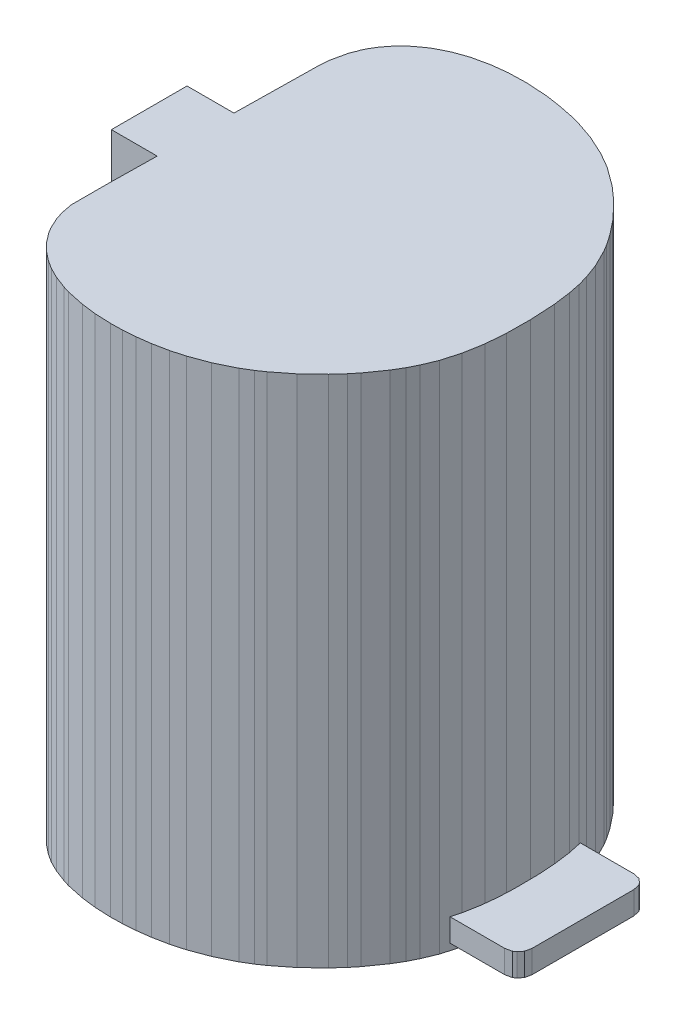
SolidWorks part; units mm, degrees
ref_plane "Front Plane" through (0, 0, 0) normal (0, 0, 1) x (1, 0, 0)
ref_plane "Top Plane" through (0, 0, 0) normal (0, 1, 0) x (1, 0, 0)
ref_plane "Right Plane" through (0, 0, 0) normal (1, 0, 0) x (0, 0, -1)
ref_plane "P1_Top_3" through (0, 3, 0) normal (0, 1, 0) x (1, 0, 0)
sketch "Sketch1" plane through (0, 3, 0) normal (0, 1, 0) x (1, 0, 0)
  line L0 (-26.8, 97.4) -> (-33.6, 96.6)
  line L1 (-33.6, 96.6) -> (-41, 95)
  line L2 (-41, 95) -> (-47.2, 92.8)
  line L3 (-47.2, 92.8) -> (-52.4, 90.2)
  line L4 (-52.4, 90.2) -> (-54.3, 89)
  line L5 (-54.3, 89) -> (-58.1, 86.2)
  line L6 (-58.1, 86.2) -> (-60.4, 84.1)
  line L7 (-60.4, 84.1) -> (-62.7, 81.6)
  line L8 (-62.7, 81.6) -> (-64.9, 78.7)
  line L9 (-64.9, 78.7) -> (-66.5, 76.1)
  line L10 (-66.5, 76.1) -> (-67.8, 73.5)
  line L11 (-67.8, 73.5) -> (-67.9, 72.9)
  line L12 (-67.9, 72.9) -> (-69.1, 70.1)
  line L13 (-69.1, 70.1) -> (-70.7, 62.9)
  line L14 (-70.7, 62.9) -> (-71, 59.1)
  line L15 (-71, 59.1) -> (-72.4, -33.1)
  line L16 (-72.4, -33.1) -> (-72.4, -48.4)
  line L17 (-72.4, -48.4) -> (-71.5, -52.9)
  line L18 (-71.5, -52.9) -> (-70.5, -56.3)
  line L19 (-70.5, -56.3) -> (-68.1, -61.5)
  line L20 (-68.1, -61.5) -> (-66.7, -63.8)
  line L21 (-66.7, -63.8) -> (-63.4, -68.1)
  line L22 (-63.4, -68.1) -> (-60.3, -71.2)
  line L23 (-60.3, -71.2) -> (-56.4, -74.3)
  line L24 (-56.4, -74.3) -> (-52.7, -76.7)
  line L25 (-52.7, -76.7) -> (-48.3, -78.9)
  line L26 (-48.3, -78.9) -> (-42.8, -81)
  line L27 (-42.8, -81) -> (-39.9, -81.9)
  line L28 (-39.9, -81.9) -> (-32.3, -83.5)
  line L29 (-32.3, -83.5) -> (-25.9, -84.3)
  line L30 (-25.9, -84.3) -> (-18.9, -84.6)
  line L31 (-18.9, -84.6) -> (-13.8, -84.5)
  line L32 (-13.8, -84.5) -> (-8.3, -84.1)
  line L33 (-8.3, -84.1) -> (-2.2, -83.3)
  line L34 (-2.2, -83.3) -> (4.3, -82)
  line L35 (4.3, -82) -> (10.1, -80.4)
  line L36 (10.1, -80.4) -> (18.2, -77.4)
  line L37 (18.2, -77.4) -> (26.2, -73.5)
  line L38 (26.2, -73.5) -> (30.5, -70.9)
  line L39 (30.5, -70.9) -> (33.7, -68.7)
  line L40 (33.7, -68.7) -> (41.1, -62.9)
  line L41 (41.1, -62.9) -> (48.1, -56.2)
  line L42 (48.1, -56.2) -> (52.1, -51.8)
  line L43 (52.1, -51.8) -> (54.7, -48.6)
  line L44 (54.7, -48.6) -> (60, -41.1)
  line L45 (60, -41.1) -> (62.6, -36.7)
  line L46 (62.6, -36.7) -> (64.6, -32.7)
  line L47 (64.6, -32.7) -> (67.1, -26.7)
  line L48 (67.1, -26.7) -> (69.3, -19)
  line L49 (69.3, -19) -> (70.8, -10.5)
  line L50 (70.8, -10.5) -> (71.5, -1.8)
  line L51 (71.5, -1.8) -> (71.6, 8.7)
  line L52 (71.6, 8.7) -> (71, 19.8)
  line L53 (71, 19.8) -> (70, 27.3)
  line L54 (70, 27.3) -> (68.9, 32.7)
  line L55 (68.9, 32.7) -> (67.7, 37)
  line L56 (67.7, 37) -> (65.4, 43.3)
  line L57 (65.4, 43.3) -> (61.7, 50.7)
  line L58 (61.7, 50.7) -> (59.9, 53.7)
  line L59 (59.9, 53.7) -> (56.9, 58.1)
  line L60 (56.9, 58.1) -> (51.6, 64.8)
  line L61 (51.6, 64.8) -> (44.6, 72.1)
  line L62 (44.6, 72.1) -> (38.7, 77.3)
  line L63 (38.7, 77.3) -> (30.5, 83.3)
  line L64 (30.5, 83.3) -> (23.9, 87.1)
  line L65 (23.9, 87.1) -> (15.6, 90.9)
  line L66 (15.6, 90.9) -> (7.7, 93.6)
  line L67 (7.7, 93.6) -> (3.5, 94.7)
  line L68 (3.5, 94.7) -> (-2.9, 96)
  line L69 (-2.9, 96) -> (-9.5, 97)
  line L70 (-9.5, 97) -> (-19.1, 97.6)
  line L71 (-19.1, 97.6) -> (-26.8, 97.4)
extrude "Bin body" add sketch "Sketch1" along normal blind 225
ref_plane "P2_Top_3" through (0, 3, 0) normal (0, 1, 0) x (1, 0, 0)
sketch "Sketch2" plane through (0, 3, 0) normal (0, 1, 0) x (1, 0, 0)
  line L0 (-92.1, 22.1) -> (-92.1, -11)
  line L1 (-92.1, -11) -> (-71.5, -11)
  line L2 (-71.5, -11) -> (-71.5, 22.1)
  line L3 (-71.5, 22.1) -> (-92.1, 22.1)
extrude "Rod channel" add sketch "Sketch2" along normal blind 225
ref_plane "P3_Top_6" through (0, 6, 0) normal (0, 1, 0) x (1, 0, 0)
sketch "Sketch3" plane through (0, 6, 0) normal (0, 1, 0) x (1, 0, 0)
  line L0 (68.8, 33.3) -> (70.1, 27.3)
  line L1 (70.1, 27.3) -> (71.1, 19.8)
  line L2 (71.1, 19.8) -> (71.6, 12.1)
  line L3 (71.6, 12.1) -> (71.7, 1.7)
  line L4 (71.7, 1.7) -> (71.4, -5.3)
  line L5 (71.4, -5.3) -> (70.7, -12)
  line L6 (70.7, -12) -> (69.4, -19)
  line L7 (69.4, -19) -> (68.3, -23.2)
  line L8 (68.3, -23.2) -> (92.2, -23.2)
  line L9 (92.2, -23.2) -> (95, -22.6)
  line L10 (95, -22.6) -> (96.2, -21.7)
  line L11 (96.2, -21.7) -> (97.6, -20)
  line L12 (97.6, -20) -> (98.2, -17.2)
  line L13 (98.2, -17.2) -> (98.2, 27.3)
  line L14 (98.2, 27.3) -> (97.6, 30.1)
  line L15 (97.6, 30.1) -> (96.7, 31.3)
  line L16 (96.7, 31.3) -> (95, 32.7)
  line L17 (95, 32.7) -> (92.2, 33.3)
  line L18 (92.2, 33.3) -> (68.8, 33.3)
extrude "Pedal pad (top 16)" add sketch "Sketch3" along normal blind 10
